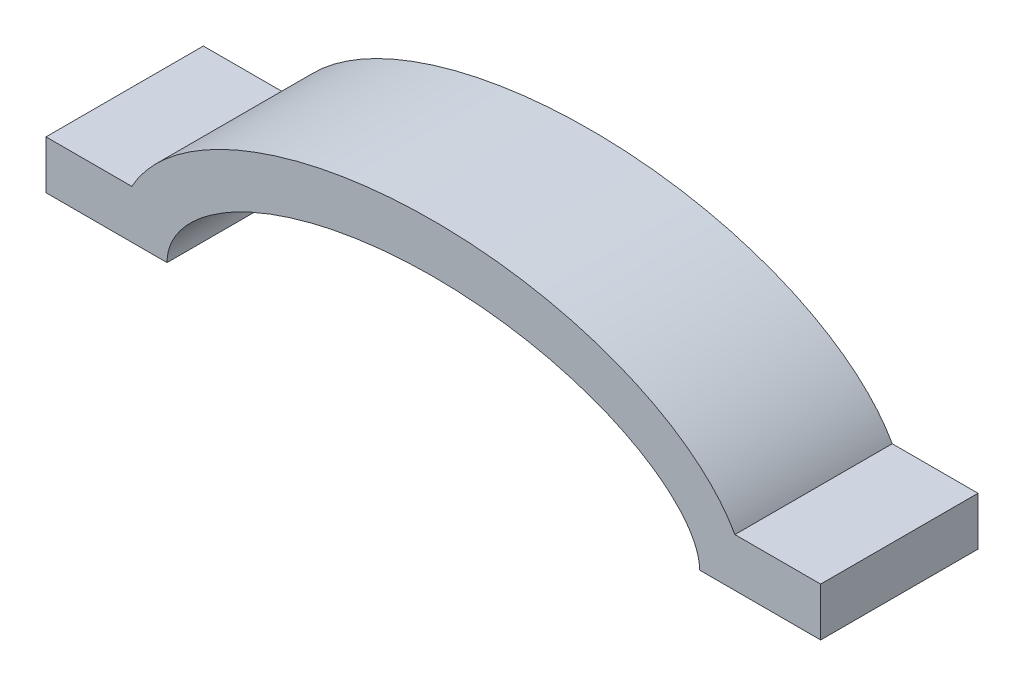
SolidWorks part; units mm, degrees
ref_plane "Front Plane" through (0, 0, 0) normal (0, 0, 1) x (1, 0, 0)
ref_plane "Top Plane" through (0, 0, 0) normal (0, 1, 0) x (1, 0, 0)
ref_plane "Right Plane" through (0, 0, 0) normal (1, 0, 0) x (0, 0, -1)
sketch "Sketch1" plane through (0, 0, 0) normal (0, 0, 1) x (1, 0, 0)
  line L3 (-22, 0) -> (-32, 0)
  line L5 (-24.9162, 4) -> (-32, 4)
  line L6 (-32, 0) -> (-32, 4)
  line L7 (22, 0) -> (32, 0)
  line L9 (24.9162, 4) -> (32, 4)
  line L10 (32, 0) -> (32, 4)
  ellipse E0 centre (0, 0) end of major axis (-26, 0) minor radius 14 (24.9162, 4) -> (-24.9162, 4) ccw
  spline S1 degree 3 poles (22, 0) (22, 0.432) (21.8549, 1.2961) (20.9974, 2.8866) (19.258, 4.6694) (15.7413, 6.9988) (9.3644, 9.3282) (0, 10.3359) (-9.3644, 9.3282) (-15.7413, 6.9988) (-19.258, 4.6694) (-20.9974, 2.8866) (-21.8549, 1.2961) (-22, 0.432) (-22, 0) knots 3.141593 3.141593 3.141593 3.141593 3.337942 3.534292 3.730641 3.926991 4.31969 4.712389 5.105088 5.497787 5.694137 5.890486 6.086836 6.283185 6.283185 6.283185 6.283185
  point P3 (-32, 0)
  point P4 (0, 14)
  point P6 (-26, 0)
  dimension "D2" = 32
  dimension "D3" = 14
  dimension "D4" = 26
  dimension "D7" = 4
  dimension "D8" = 32
extrude "Boss-Extrude4" add sketch "Sketch1" along normal blind 13
